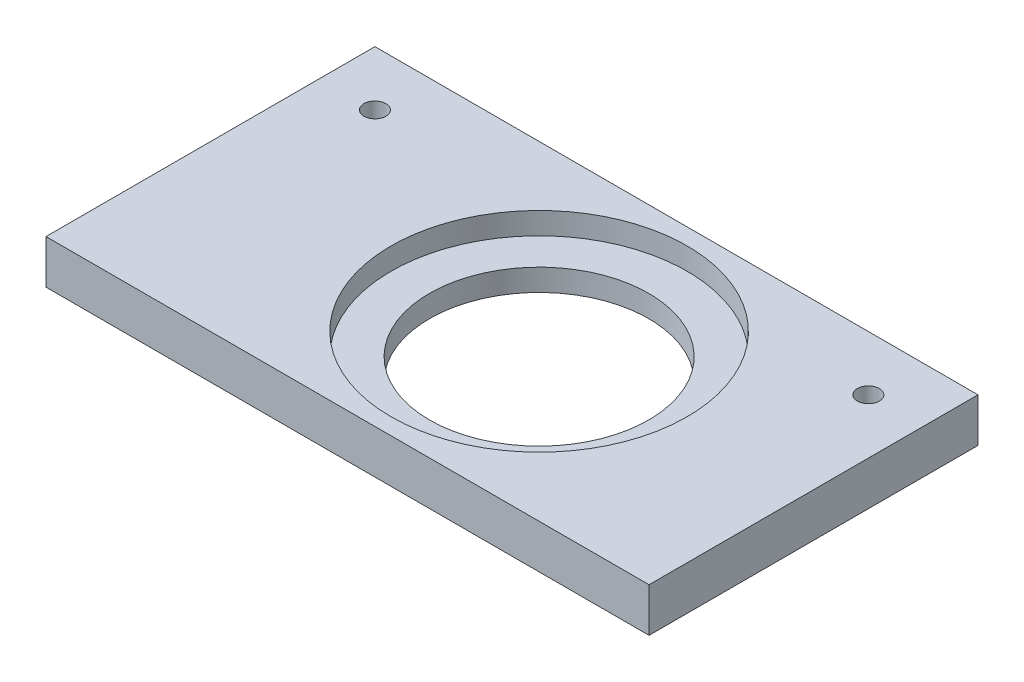
SolidWorks part; units mm, degrees
ref_plane "Front Plane" through (0, 0, 0) normal (0, 0, 1) x (1, 0, 0)
ref_plane "Top Plane" through (0, 0, 0) normal (0, 1, 0) x (1, 0, 0)
ref_plane "Right Plane" through (0, 0, 0) normal (1, 0, 0) x (0, 0, -1)
sketch "Sketch1" plane through (0, 0, 0) normal (0, 1, 0) x (1, 0, 0)
  line L1 (-149.86, -75) -> (125.14, -75)
  line L2 (-149.86, -75) -> (-149.86, 75)
  line L3 (-149.86, 75) -> (125.14, 75)
  line L4 (125.14, -75) -> (125.14, 75)
  circle A0 centre (0, 0) radius 5
  point P0 (0, 0)
  point P8 (-149.86, 0)
  point P10 (-127.8479, 27.7873)
  dimension "D3" = 10
  dimension "D1" = 150
  dimension "D2" = 275
  dimension "D4" = 149.86
extrude "Boss-Extrude1" add sketch "Sketch1" along normal blind 20
sketch "Sketch2" plane through (0, 20, 0) normal (0, 1, 0) x (1, 0, 0)
  circle A0 centre (0, 0) radius 50
  dimension "D1" = 100
extrude "Cut-Extrude1" cut sketch "Sketch2" against normal through all
sketch "Sketch3" plane through (0, 20, 0) normal (0, 1, 0) x (1, 0, 0)
  circle A0 centre (0, 0) radius 67.5
  dimension "D1" = 135
extrude "Cut-Extrude2" cut sketch "Sketch3" against normal blind 10
sketch "Sketch4" plane through (0, 20, 0) normal (0, 1, 0) x (1, 0, 0)
  line L0 (125.14, 50) -> (-149.86, 50) construction
  line L1 (125.14, -75) -> (125.14, 75) construction
  line L2 (-149.86, 75) -> (-149.86, -75) construction
  line L3 (125.14, 75) -> (-149.86, 75) construction
  line L4 (-12.36, 75) -> (-12.36, -75) construction
  line L5 (-149.86, -75) -> (125.14, -75) construction
  circle A0 centre (100.14, 50) radius 5
  circle A1 centre (-124.86, 50) radius 5
  dimension "D2" = 25
  dimension "D3" = 10
  dimension "D1" = 25
extrude "Cut-Extrude3" cut sketch "Sketch4" against normal through all
sketch "Sketch5" plane through (0, 0, 0) normal (0, -1, 0) x (1, 0, 0)
  line L0 (125.14, -75) -> (-149.86, -75) construction
  line L1 (-99.86, -75) -> (-80.81, -75)
  line L2 (-99.86, -75) -> (-99.86, -68.52)
  line L3 (-99.86, -68.52) -> (-80.81, -68.52)
  line L4 (-80.81, -75) -> (-80.81, -68.52)
  line L5 (-149.86, -75) -> (-149.86, 75) construction
  line L6 (56.09, -75) -> (75.14, -75)
  line L7 (56.09, -75) -> (56.09, -68.52)
  line L8 (56.09, -68.52) -> (75.14, -68.52)
  line L9 (75.14, -75) -> (75.14, -68.52)
  line L10 (125.14, 75) -> (125.14, -75) construction
  dimension "D1" = 19.05
  dimension "D2" = 6.48
  dimension "D3" = 50
  dimension "D4" = 50
extrude "Cut-Extrude4" cut sketch "Sketch5" against normal blind 0.64
hole_wizard "M2 Clearance Hole1" positions "Sketch6" profile "Sketch7" hole size "M2" standard "ANSI Metric"
sketch "Sketch6" plane through (0, 0.64, 0) normal (0, -1, 0) x (-1, 0, 0)
  line L0 (-71.18, 71.76) -> (-60.05, 71.76) construction
  line L2 (84.77, 71.76) -> (95.9, 71.76) construction
  line L4 (99.86, 75) -> (80.81, 75) construction
  line L5 (-56.09, 75) -> (-75.14, 75) construction
  line L6 (-75.14, 75) -> (-75.14, 68.52) construction
  line L7 (80.81, 75) -> (80.81, 68.52) construction
  point P0 (95.9, 71.76)
  point P2 (84.77, 71.76)
  point P4 (-71.18, 71.76)
  point P6 (-60.2096, 71.76)
  point P18 (90.335, 75)
  point P19 (90.335, 71.76)
  point P22 (-65.615, 75)
  point P23 (-65.615, 71.76)
  point P26 (-75.14, 71.76)
  point P29 (80.81, 71.76)
  dimension "D1" = 11.13
sketch "Sketch7" plane through (-95.9, 0.64, -71.76) normal (1, 0, 0) x (0, 0, -1)
  line L0 (0, 0) -> (0, 2.7811)
  line L1 (0, 2.7811) -> (1.3, 2)
  line L2 (1.3, 2) -> (1.3, 0)
  line L5 (1.3, 0) -> (0, 0)
  line L10 (0, 2.7811) -> (-1.3, 2) construction
  line L11 (0, -6.35) -> (0, 107.95) construction
  dimension "Hole Dia." = 2.6
  dimension "Hole Depth" = 2
  dimension "Drill Angle" = 118
